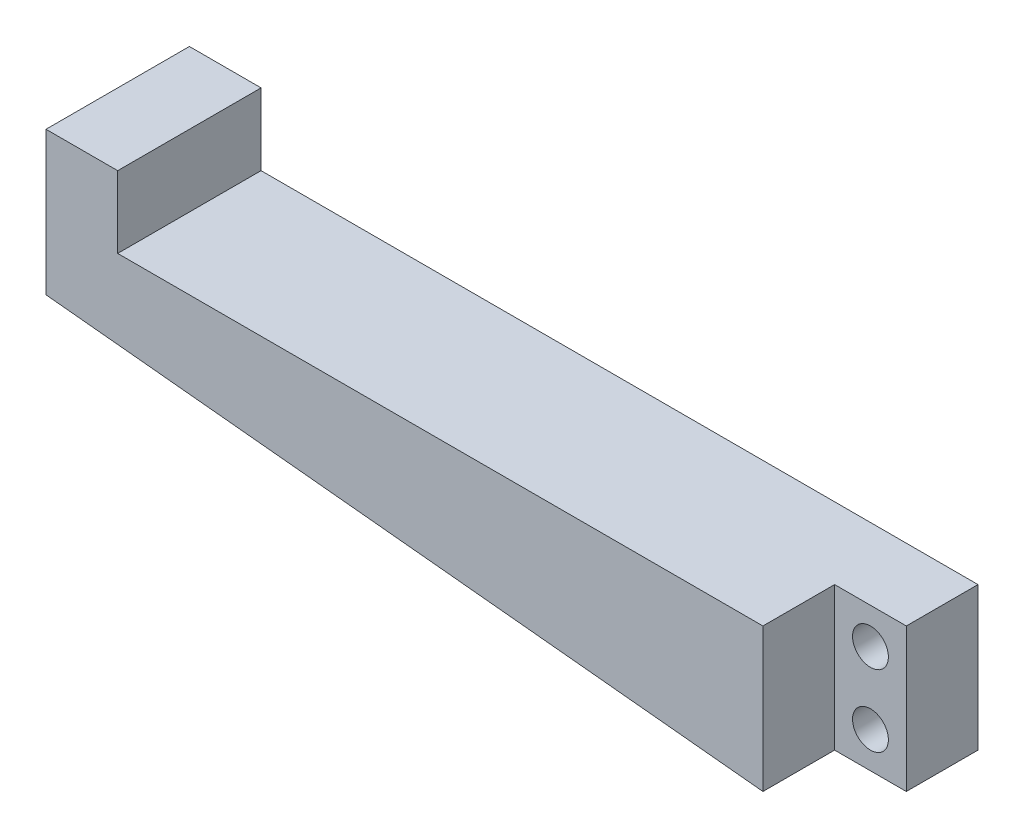
SolidWorks part; units mm, degrees
ref_plane "Plan de face" through (0, 0, 0) normal (0, 0, 1) x (1, 0, 0)
ref_plane "Plan de dessus" through (0, 0, 0) normal (0, 1, 0) x (1, 0, 0)
ref_plane "Plan de droite" through (0, 0, 0) normal (1, 0, 0) x (0, 0, -1)
sketch "Esquisse1" plane through (0, 0, 0) normal (0, 0, 1) x (1, 0, 0)
  line L0 (-105, 0) -> (-5, -10)
  line L1 (-5, -10) -> (5, -10)
  line L3 (-5, 10) -> (5, 10)
  line L4 (5, -10) -> (5, 10)
  line L5 (-5, -10) -> (5, 10) construction
  line L6 (-5, 10) -> (5, -10) construction
  line L7 (-5, 10) -> (-95, 10)
  line L10 (-105, 10) -> (-105, 0)
  line L12 (-105, 10) -> (-105, 20)
  line L13 (-105, 20) -> (-95, 20)
  line L14 (-95, 10) -> (-95, 20)
  circle A0 centre (0, 5) radius 2.5
  circle A1 centre (0, -5) radius 2.5
  point P0 (0, 0)
  dimension "D2" = 5
  dimension "D6" = 5
  dimension "D1" = 20
  dimension "D3" = 10
  dimension "D4" = 5
  dimension "D5" = 5
  dimension "D7" = 100
  dimension "D8" = 10
  dimension "D9" = 10
  dimension "D10" = 10
extrude "Boss.-Extru.1" add sketch "Esquisse1" along normal blind 20
sketch "Esquisse2" plane through (0, 0, 20) normal (0, 0, 1) x (1, 0, 0)
  line L1 (-5, -10) -> (5, -10)
  line L2 (-5, -10) -> (-5, 10)
  line L3 (-5, 10) -> (5, 10)
  line L4 (5, -10) -> (5, 10)
extrude "Enlèv. mat.-Extru.1" cut sketch "Esquisse2" against normal blind 10
